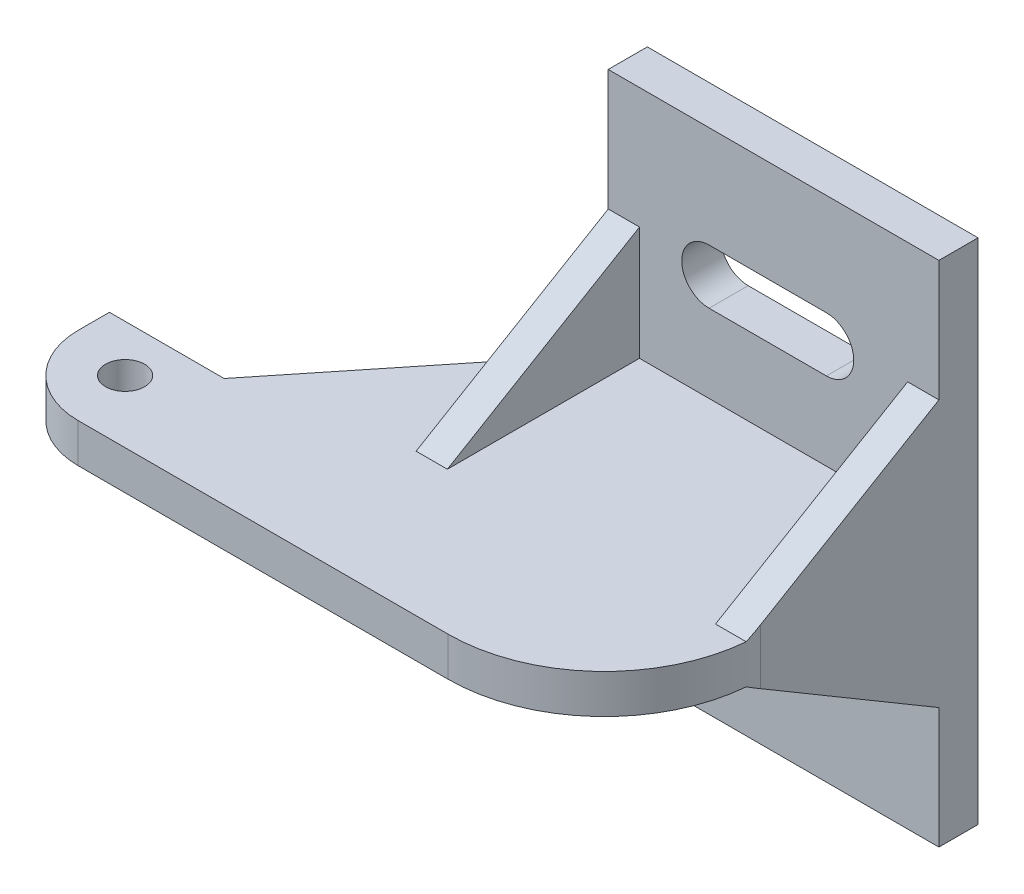
SolidWorks part; units mm, degrees
ref_plane "Front Plane" through (0, 0, 0) normal (0, 0, 1) x (1, 0, 0)
ref_plane "Top Plane" through (0, 0, 0) normal (0, 1, 0) x (1, 0, 0)
ref_plane "Right Plane" through (0, 0, 0) normal (1, 0, 0) x (0, 0, -1)
sketch "Sketch1" plane through (0, 0, 0) normal (0, 1, 0) x (1, 0, 0)
  line L0 (-10.2553, 42.8084) -> (11.7447, 42.8084)
  line L2 (-20.4053, 3.0084) -> (-20.4053, -4.9916)
  line L3 (-20.4053, -4.9916) -> (21.8947, -4.9916)
  line L4 (21.8947, 3.0084) -> (21.8947, -4.9916)
  line L5 (0, 0) -> (21.8947, -4.9916) construction
  line L6 (-20.4053, -4.9916) -> (0, 0) construction
  line L8 (-20.4053, 3.0084) -> (-20.4053, 42.8084)
  line L9 (-20.4053, 42.8084) -> (-10.2553, 42.8084)
  line L12 (21.8947, 3.0084) -> (21.8947, 42.8084)
  line L13 (21.8947, 42.8084) -> (11.7447, 42.8084)
  point P0 (0, 0)
  dimension "D1" = 42.3
  dimension "D2" = 47.8
  dimension "D5" = 4.9916
extrude "Boss-Extrude1" add sketch "Sketch1" along normal blind 5
sketch "Sketch5" plane through (0, 5, 0) normal (0, 1, 0) x (1, 0, 0)
  line L3 (21.8947, 37.8084) -> (-20.4053, 37.8084)
  line L5 (21.8947, 37.8084) -> (21.8947, 42.8084)
  line L7 (21.8947, 42.8084) -> (-20.4053, 42.8084)
  line L8 (-20.4053, 37.8084) -> (-20.4053, 42.8084)
extrude "Boss-Extrude4" add sketch "Sketch5" against normal blind 35 and the other way blind 30
sketch "Sketch8" plane through (0, 0, -37.8084) normal (0, 0, 1) x (1, 0, 0)
  line L0 (-7.5, 18.5) -> (7.5, 18.5) construction
  line L1 (-7.5, 22) -> (7.5, 22)
  line L2 (-7.5, 15) -> (7.5, 15)
  line L3 (-7.5, -13.5) -> (7.5, -13.5) construction
  line L4 (-7.5, -10) -> (7.5, -10)
  line L5 (-7.5, -17) -> (7.5, -17)
  line L6 (-20.4053, 0) -> (21.8947, 0) construction
  line L7 (-20.4053, 5) -> (21.8947, 5) construction
  line L10 (0, 0) -> (0, 70.027) construction
  arc A0 (-7.5, 22) -> (-7.5, 15) centre (-7.5, 18.5) ccw
  arc A1 (7.5, 15) -> (7.5, 22) centre (7.5, 18.5) ccw
  arc A2 (-7.5, -10) -> (-7.5, -17) centre (-7.5, -13.5) ccw
  arc A3 (7.5, -17) -> (7.5, -10) centre (7.5, -13.5) ccw
  point P2 (0, 18.5)
  point P9 (0, -13.5)
  dimension "D1" = 3.5
  dimension "D3" = 10
  dimension "D4" = 0
  dimension "D6" = 15
  dimension "D2" = 10
extrude "Cut-Extrude5" cut sketch "Sketch8" against normal blind 10
sketch "Sketch9" plane through (-20.4053, 0, 0) normal (-1, 0, 0) x (0, 0, 1)
  line L0 (-37.8084, 0) -> (4.9916, 0) construction
  line L1 (4.9916, 5) -> (-9.0084, 5)
  line L2 (4.9916, 5) -> (4.9916, 0)
  line L3 (4.9916, 0) -> (-9.0084, 0)
  line L4 (-9.0084, 5) -> (-9.0084, 0)
  dimension "D1" = 14
extrude "Boss-Extrude5" add sketch "Sketch9" along normal blind 35
fillet "Fillet1" radius 10 1 edges at (-55.4053, 2.5, 4.9916)
sketch "Sketch10" plane through (-20.4053, 0, 0) normal (-1, 0, 0) x (0, 0, 1)
  line L0 (-42.8084, 2.5) -> (-42.8084, 22.5)
  line L1 (-42.8084, 35) -> (-42.8084, -30) construction
  line L2 (-42.8084, 22.5) -> (-9.0084, 2.5)
  line L3 (-9.0084, 5) -> (-9.0084, 0) construction
  line L4 (-9.0084, 2.5) -> (-42.8084, -17.5)
  line L5 (-42.8084, -17.5) -> (-42.8084, 2.5)
  dimension "D1" = 20
  dimension "D2" = 20
extrude "Boss-Extrude6" add sketch "Sketch10" against normal blind 4
sketch "Sketch11" plane through (21.8947, 0, 0) normal (1, 0, 0) x (0, 0, -1)
  line L0 (37.8084, 19.5414) -> (37.8084, -14.5414)
  line L1 (37.8084, -14.5414) -> (13.2334, 0)
  line L2 (13.2334, 0) -> (13.2334, 5)
  line L3 (13.2334, 5) -> (37.8084, 19.5414)
extrude "Boss-Extrude7" add sketch "Sketch11" against normal blind 4
sketch "Sketch12" plane through (0, 5, 0) normal (0, 1, 0) x (1, 0, 0)
  line L0 (-55.4053, 5.0084) -> (-55.4053, 9.0084) construction
  line L1 (-45.4053, -4.9916) -> (21.8947, -4.9916) construction
  circle A0 centre (-47.4053, 3.0084) radius 2.5
  point P0 (-47.4053, 3.0084)
  point P1 (-55.4053, 7.0084)
  dimension "D3" = 5
  dimension "D1" = 8
  dimension "D2" = 8
extrude "Cut-Extrude6" cut sketch "Sketch12" against normal through all
sketch "Sketch13" plane through (0, 0, 0) normal (0, -1, 0) x (1, 0, 0)
  line L0 (-40.7331, -9.0084) -> (-20.4053, -34.3256)
  line L1 (-55.4053, -9.0084) -> (-20.4053, -9.0084) construction
  line L2 (-20.4053, -34.3256) -> (-20.4053, -9.0084)
  line L3 (-20.4053, -9.0084) -> (-40.7331, -9.0084)
extrude "Boss-Extrude8" add sketch "Sketch13" against normal blind 5
fillet "Fillet2" radius 20 1 edges at (21.8947, 2.5, 4.9916)
equation "\"26..50mm\"=27"
